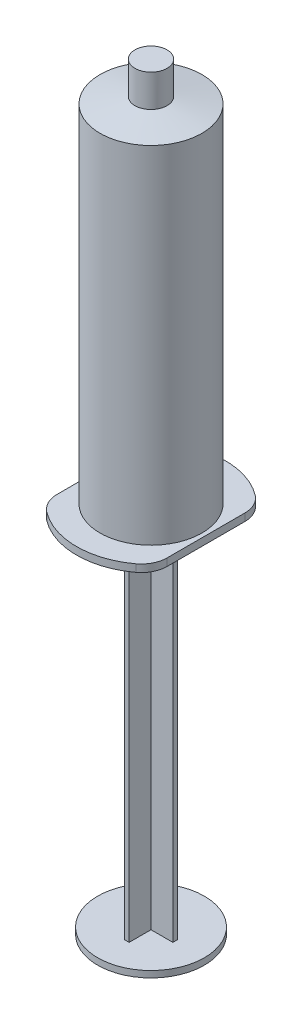
SolidWorks part; units mm, degrees
material "PPE"
ref_plane "Front Plane" through (0, 0, 0) normal (0, 0, 1) x (1, 0, 0)
ref_plane "Top Plane" through (0, 0, 0) normal (0, 1, 0) x (1, 0, 0)
ref_plane "Right Plane" through (0, 0, 0) normal (1, 0, 0) x (0, 0, -1)
sketch "Sketch1" plane through (0, 0, 0) normal (0, 1, 0) x (1, 0, 0)
  circle A0 centre (0, 0) radius 15.75
  dimension "D1" = 31.5
extrude "Boss-Extrude1" add sketch "Sketch1" along normal blind 109
chamfer "Chamfer1" distance 2 angle 79.5 1 edges at (0, 109, 15.75)
sketch "Sketch2" plane through (0, 109, 0) normal (0, 1, 0) x (1, 0, 0)
  circle A0 centre (0, 0) radius 4.959 construction
  circle A1 centre (0, 0) radius 4.959
extrude "Boss-Extrude2" add sketch "Sketch2" along normal blind 10
sketch "Sketch3" plane through (0, 0, 0) normal (0, -1, 0) x (1, 0, 0)
  line L0 (-17, 12) -> (-17, -12)
  line L1 (17, 12) -> (17, -12)
  arc A0 (-13.8, -18.4) -> (13.8, -18.4) centre (0, 0) ccw
  arc A1 (13.8, 18.4) -> (-13.8, 18.4) centre (0, 0) ccw
  arc A2 (-17, -12) -> (-13.8, -18.4) centre (-9, -12) ccw
  arc A3 (17, -12) -> (13.8, -18.4) centre (9, -12) cw
  arc A4 (17, 12) -> (13.8, 18.4) centre (9, 12) ccw
  arc A5 (-17, 12) -> (-13.8, 18.4) centre (-9, 12) cw
  point P12 (17, 15.4919)
  dimension "D1" = 46
  dimension "D3" = 8
  dimension "D2" = 34
extrude "Boss-Extrude3" add sketch "Sketch3" along normal blind 2.3
sketch "Sketch4" plane through (0, -2.3, 0) normal (0, -1, 0) x (1, 0, 0)
  line L0 (0.75, 0.75) -> (7.5, 0.75)
  line L1 (-0.75, -7.5) -> (0.75, -7.5)
  line L2 (-0.75, -7.5) -> (-0.75, -0.75)
  line L3 (-0.75, 7.5) -> (0.75, 7.5)
  line L4 (0.75, -7.5) -> (0.75, -0.75)
  line L5 (-0.75, -7.5) -> (0.75, 7.5) construction
  line L6 (-0.75, 7.5) -> (0.75, -7.5) construction
  line L7 (-7.5, 0.75) -> (-0.75, 0.75)
  line L8 (-7.5, 0.75) -> (-7.5, -0.75)
  line L9 (-7.5, -0.75) -> (-0.75, -0.75)
  line L10 (7.5, 0.75) -> (7.5, -0.75)
  line L11 (-7.5, 0.75) -> (7.5, -0.75) construction
  line L12 (-7.5, -0.75) -> (7.5, 0.75) construction
  line L13 (-0.75, 0.75) -> (-0.75, 7.5)
  line L16 (0.75, -0.75) -> (7.5, -0.75)
  line L18 (0.75, 0.75) -> (0.75, 7.5)
  point P0 (0, 0)
  point P7 (0, 0)
  dimension "D1" = 1.5
  dimension "D2" = 15
extrude "Boss-Extrude4" add sketch "Sketch4" along normal blind 111
sketch "Sketch5" plane through (0, -113.3, 0) normal (0, -1, 0) x (1, 0, 0)
  circle A0 centre (0, 0) radius 16.5
  dimension "D1" = 33
extrude "Boss-Extrude5" add sketch "Sketch5" along normal blind 2
